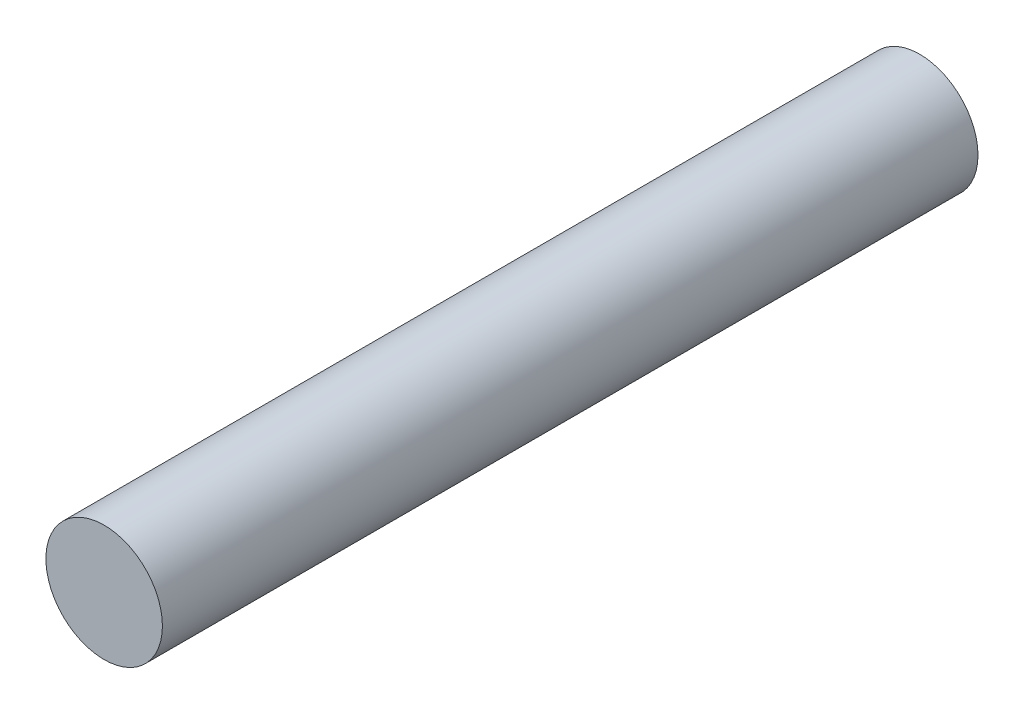
SolidWorks part; units mm, degrees
ref_plane "Front Plane" through (0, 0, 0) normal (0, 0, 1) x (1, 0, 0)
ref_plane "Top Plane" through (0, 0, 0) normal (0, 1, 0) x (1, 0, 0)
ref_plane "Right Plane" through (0, 0, 0) normal (1, 0, 0) x (0, 0, -1)
sketch "Sketch1" plane through (0, 0, 0) normal (0, 0, 1) x (1, 0, 0)
  circle A0 centre (0, 0) radius 1
  dimension "D1" = 2
extrude "Boss-Extrude1" add sketch "Sketch1" along normal blind 14
